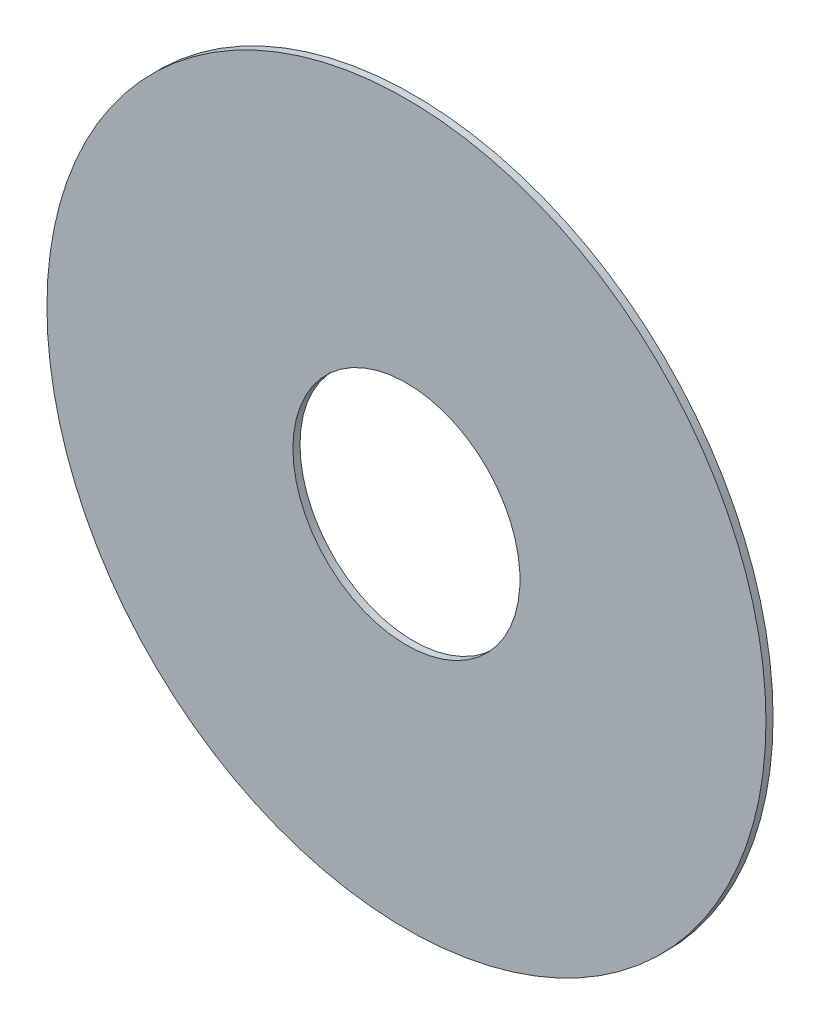
SolidWorks part; units mm, degrees
ref_plane "Front Plane" through (0, 0, 0) normal (0, 0, 1) x (1, 0, 0)
ref_plane "Top Plane" through (0, 0, 0) normal (0, 1, 0) x (1, 0, 0)
ref_plane "Right Plane" through (0, 0, 0) normal (1, 0, 0) x (0, 0, -1)
sketch "Sketch1" plane through (0, 0, 0) normal (0, 0, 1) x (1, 0, 0)
  circle A0 centre (0, 0) radius 241.3
  circle A1 centre (0, 0) radius 76.2
extrude "Boss-Extrude1" add sketch "Sketch1" along normal blind 4.7625
